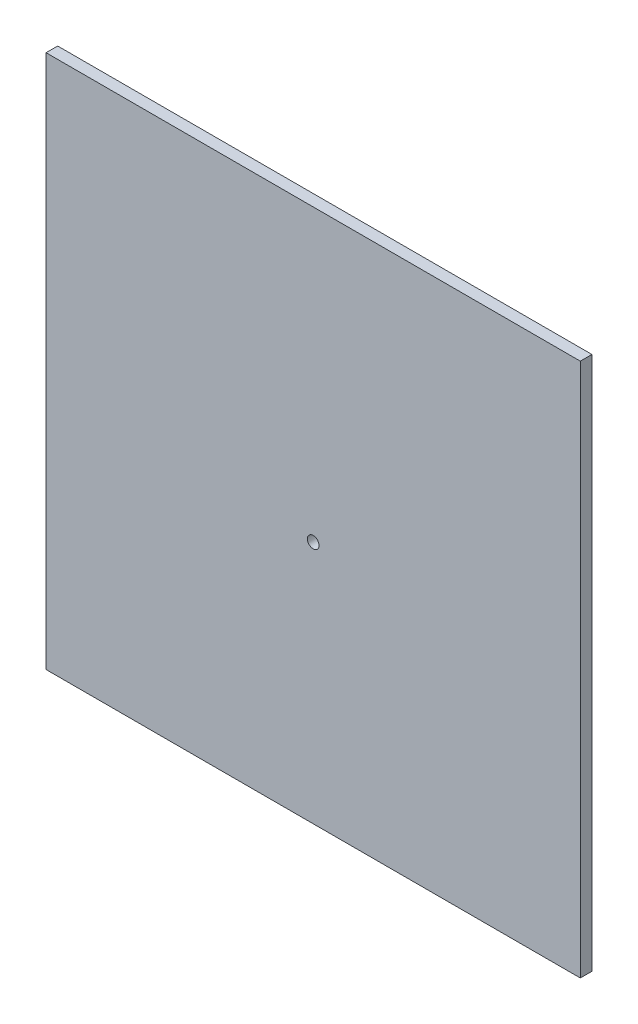
SolidWorks part; units mm, degrees
material "Acrylic (Medium-high impact)"
ref_plane "Front Plane" through (0, 0, 0) normal (0, 0, 1) x (1, 0, 0)
ref_plane "Top Plane" through (0, 0, 0) normal (0, 1, 0) x (1, 0, 0)
ref_plane "Right Plane" through (0, 0, 0) normal (1, 0, 0) x (0, 0, -1)
sketch "Sketch1" plane through (0, 0, 0) normal (0, 0, 1) x (1, 0, 0)
  line L1 (0, 0) -> (584.2, 0)
  line L2 (0, 0) -> (0, 584.2)
  line L3 (0, 584.2) -> (584.2, 584.2)
  line L4 (584.2, 0) -> (584.2, 584.2)
  circle A0 centre (292.1, 266.7) radius 6.35
  dimension "D3" = 12.7
  dimension "D1" = 584.2
  dimension "D2" = 584.2
  dimension "D4" = 292.1
  dimension "D5" = 266.7
extrude "Boss-Extrude1" add sketch "Sketch1" along normal blind 12.7
